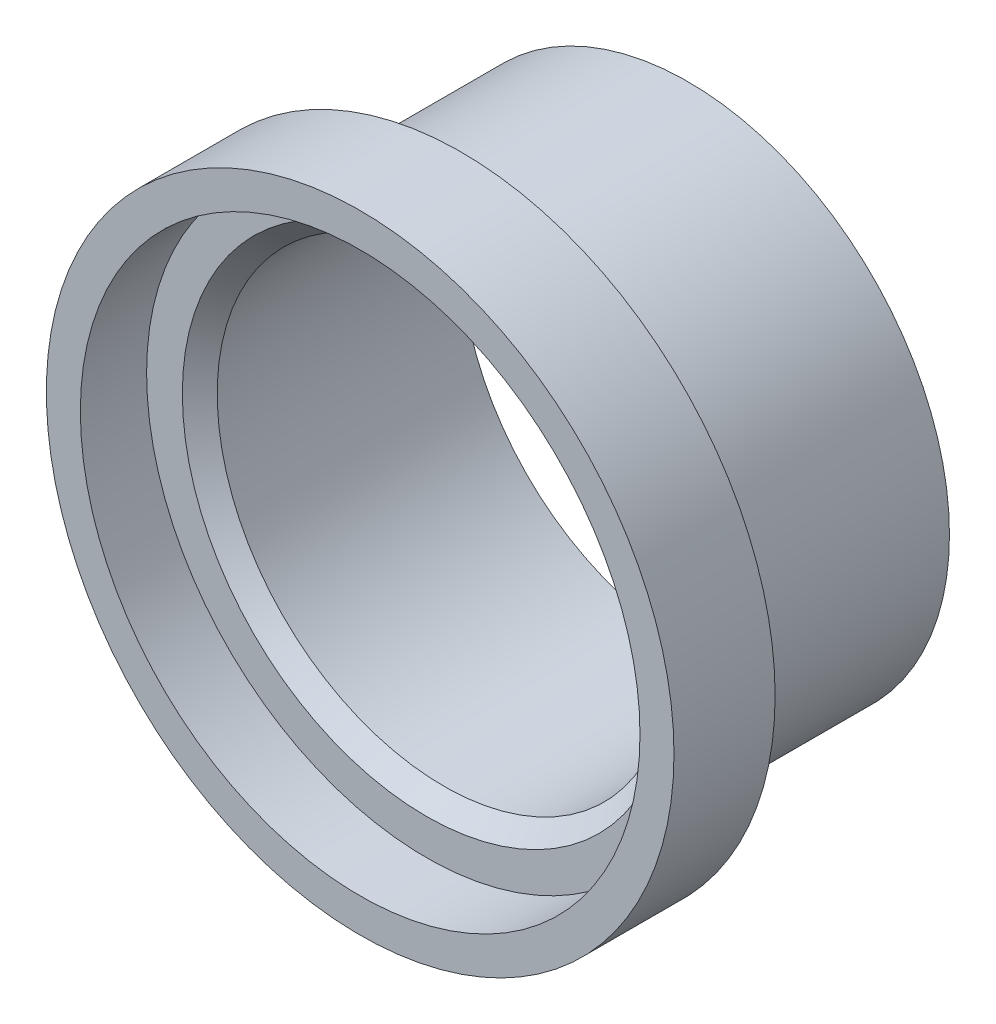
SolidWorks part; units mm, degrees
ref_plane "Front Plane" through (0, 0, 0) normal (0, 0, 1) x (1, 0, 0)
ref_plane "Top Plane" through (0, 0, 0) normal (0, 1, 0) x (1, 0, 0)
ref_plane "Right Plane" through (0, 0, 0) normal (1, 0, 0) x (0, 0, -1)
sketch "Sketch1" plane through (0, 0, 0) normal (0, 0, 1) x (1, 0, 0)
  circle A0 centre (0, 0) radius 15
  circle A1 centre (0, 0) radius 13
  dimension "D1" = 30
  dimension "D2" = 2
extrude "Boss-Extrude1" add sketch "Sketch1" along normal up to surface (13 mm away)
sketch "Sketch2" plane through (0, 0, 13) normal (0, 0, 1) x (1, 0, 0)
  circle A0 centre (0, 0) radius 13 construction
  circle A1 centre (0, 0) radius 13
  circle A2 centre (0, 0) radius 18
  dimension "D1" = 36
extrude "Boss-Extrude2" add sketch "Sketch2" along normal blind 2
chamfer "Chamfer1" distance 1 angle 45 1 edges at (13, 0, 15)
sketch "Sketch4" plane through (0, 0, 15) normal (0, 0, 1) x (1, 0, 0)
  circle A0 centre (0, 0) radius 18 construction
  circle A1 centre (0, 0) radius 18
  circle A2 centre (0, 0) radius 16.05
  dimension "D1" = 32.1
extrude "Boss-Extrude3" add sketch "Sketch4" along normal blind 3.8
sketch "Sketch5" plane through (0, 0, 0) normal (0, 0, -1) x (-1, 0, 0)
  circle A1 centre (0, 0) radius 15
  circle A2 centre (0, 0) radius 15
  dimension "D1" = 0
extrude "Boss-Extrude4" [suppressed] add sketch "Sketch5" against normal blind 2
